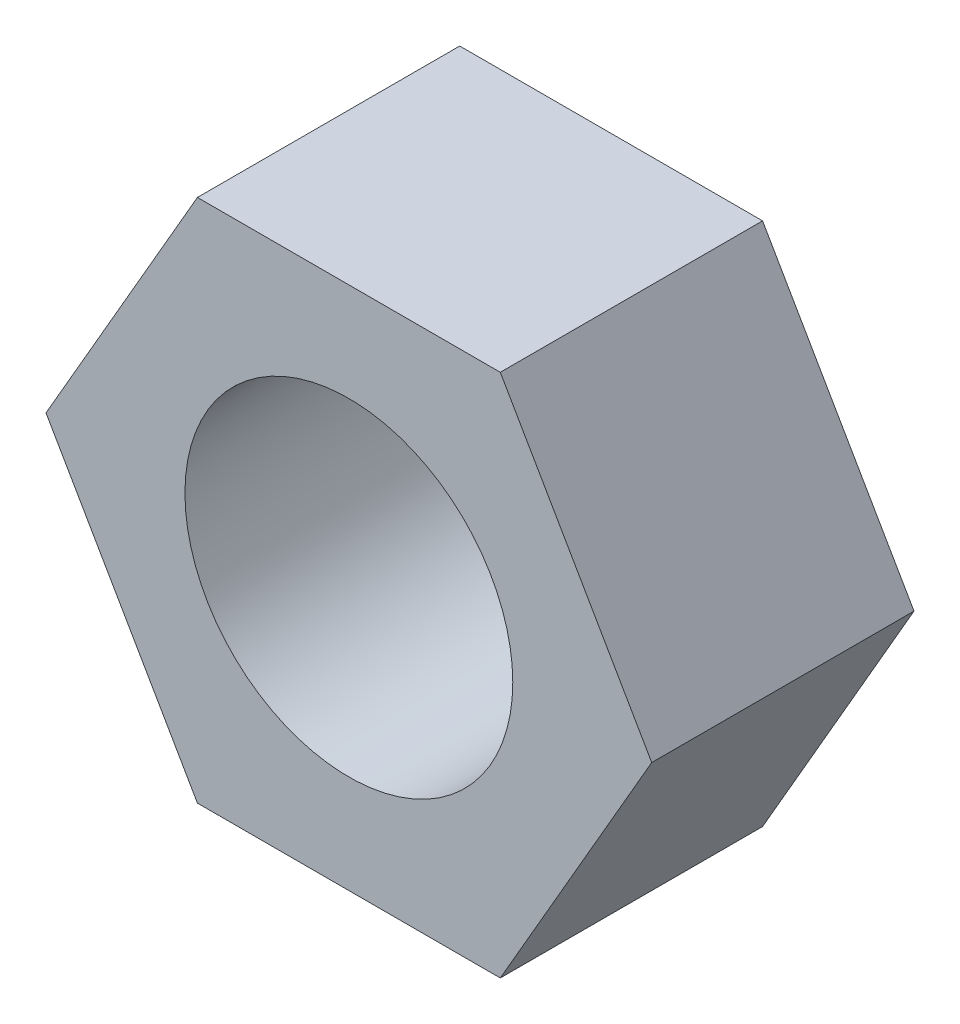
SolidWorks part; units mm, degrees
ref_plane "Front Plane" through (0, 0, 0) normal (0, 0, 1) x (1, 0, 0)
ref_plane "Top Plane" through (0, 0, 0) normal (0, 1, 0) x (1, 0, 0)
ref_plane "Right Plane" through (0, 0, 0) normal (1, 0, 0) x (0, 0, -1)
sketch "Sketch1" plane through (0, 0, 0) normal (0, 0, 1) x (1, 0, 0)
  line L0 (4.6188, 0) -> (2.3094, 4)
  line L1 (2.3094, 4) -> (-2.3094, 4)
  line L2 (-2.3094, 4) -> (-4.6188, 0)
  line L3 (-4.6188, 0) -> (-2.3094, -4)
  line L4 (-2.3094, -4) -> (2.3094, -4)
  line L5 (2.3094, -4) -> (4.6188, 0)
extrude "Hex" add sketch "Sketch1" along normal blind 4
sketch "Sketch2" plane through (0, 0, 0) normal (0, 0, 1) x (1, 0, 0)
  circle A0 centre (0, 0) radius 2.5
extrude "Bore" cut sketch "Sketch2" along normal blind 4
